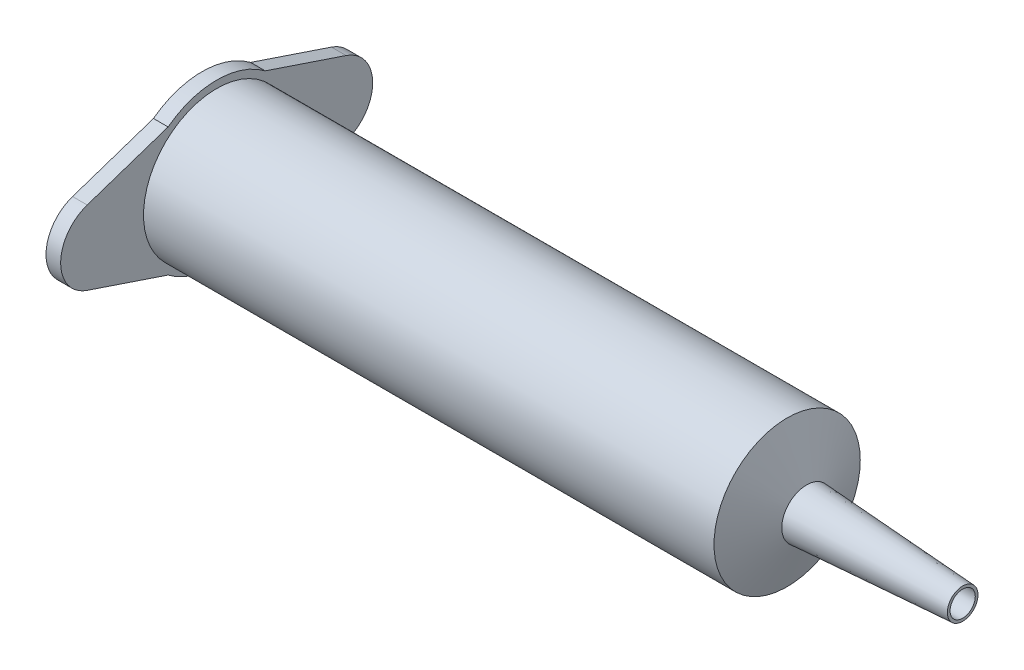
SolidWorks part; units mm, degrees
ref_plane "Front Plane" through (0, 0, 0) normal (0, 0, 1) x (1, 0, 0)
ref_plane "Top Plane" through (0, 0, 0) normal (0, 1, 0) x (1, 0, 0)
ref_plane "Right Plane" through (0, 0, 0) normal (1, 0, 0) x (0, 0, -1)
sketch "Sketch1" plane through (0, 0, 0) normal (1, 0, 0) x (0, 0, -1)
  circle A0 centre (0, 0) radius 15
  dimension "D1" = 30
extrude "Boss-Extrude1" add sketch "Sketch1" along normal blind 117
sketch "Sketch2" plane through (117, 0, 0) normal (1, 0, 0) x (0, 0, -1)
  circle A0 centre (0, 0) radius 15
extrude "Boss-Extrude2" add sketch "Sketch2" along normal blind 4 draft 68
sketch "Sketch3" plane through (121, 0, 0) normal (1, 0, 0) x (0, 0, -1)
  circle A0 centre (0, 0) radius 5.0997
extrude "Boss-Extrude3" add sketch "Sketch3" along normal blind 32 draft 3.5
sketch "Sketch4" plane through (0, 0, 0) normal (-1, 0, 0) x (0, 0, 1)
  line L3 (9.9601, -13.1547) -> (26.5471, -7.5837)
  line L5 (26.5471, 7.5837) -> (9.9601, 13.1547)
  line L6 (-9.9601, 13.1547) -> (-26.5471, 7.5837)
  line L8 (-26.5471, -7.5837) -> (-9.9601, -13.1547)
  arc A0 (9.9601, 13.1547) -> (-9.9601, 13.1547) centre (0, 0) ccw
  arc A1 (26.5471, -7.5837) -> (26.5471, 7.5837) centre (24, 0) ccw
  arc A2 (-26.5471, 7.5837) -> (-26.5471, -7.5837) centre (-24, 0) ccw
  arc A3 (-9.9601, -13.1547) -> (9.9601, -13.1547) centre (0, 0) ccw
  point P5 (0, 0)
extrude "Boss-Extrude4" add sketch "Sketch4" along normal blind 3
sketch "Sketch5" plane through (-3, 0, 0) normal (-1, 0, 0) x (0, 0, 1)
  circle A0 centre (0, 0) radius 14
extrude "Cut-Extrude1" cut sketch "Sketch5" against normal blind 117
sketch "Sketch6" plane through (153, 0, 0) normal (1, 0, 0) x (0, 0, -1)
  circle A0 centre (0, 0) radius 2.5839
extrude "Cut-Extrude2" cut sketch "Sketch6" against normal blind 117
